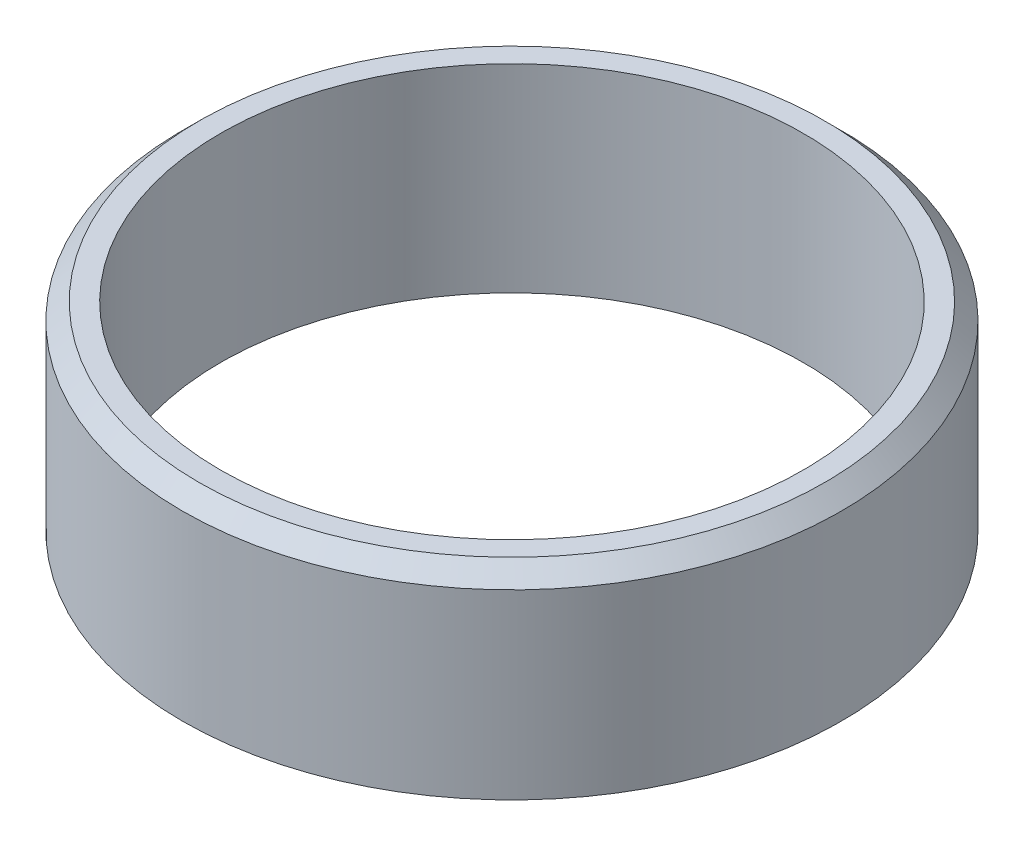
SolidWorks part; units mm, degrees
ref_plane "Front Plane" through (0, 0, 0) normal (0, 0, 1) x (1, 0, 0)
ref_plane "Top Plane" through (0, 0, 0) normal (0, 1, 0) x (1, 0, 0)
ref_plane "Right Plane" through (0, 0, 0) normal (1, 0, 0) x (0, 0, -1)
sketch "Sketch1" plane through (0, 0, 0) normal (0, 1, 0) x (1, 0, 0)
  circle A0 centre (0, 0) radius 19.925
  circle A1 centre (0, 0) radius 17.625
  dimension "D1" = 39.85
  dimension "D2" = 2.3
extrude "Boss-Extrude1" add sketch "Sketch1" along normal blind 12
chamfer "Chamfer1" distance 1 angle 45 1 edges at (0, 12, 19.925)
